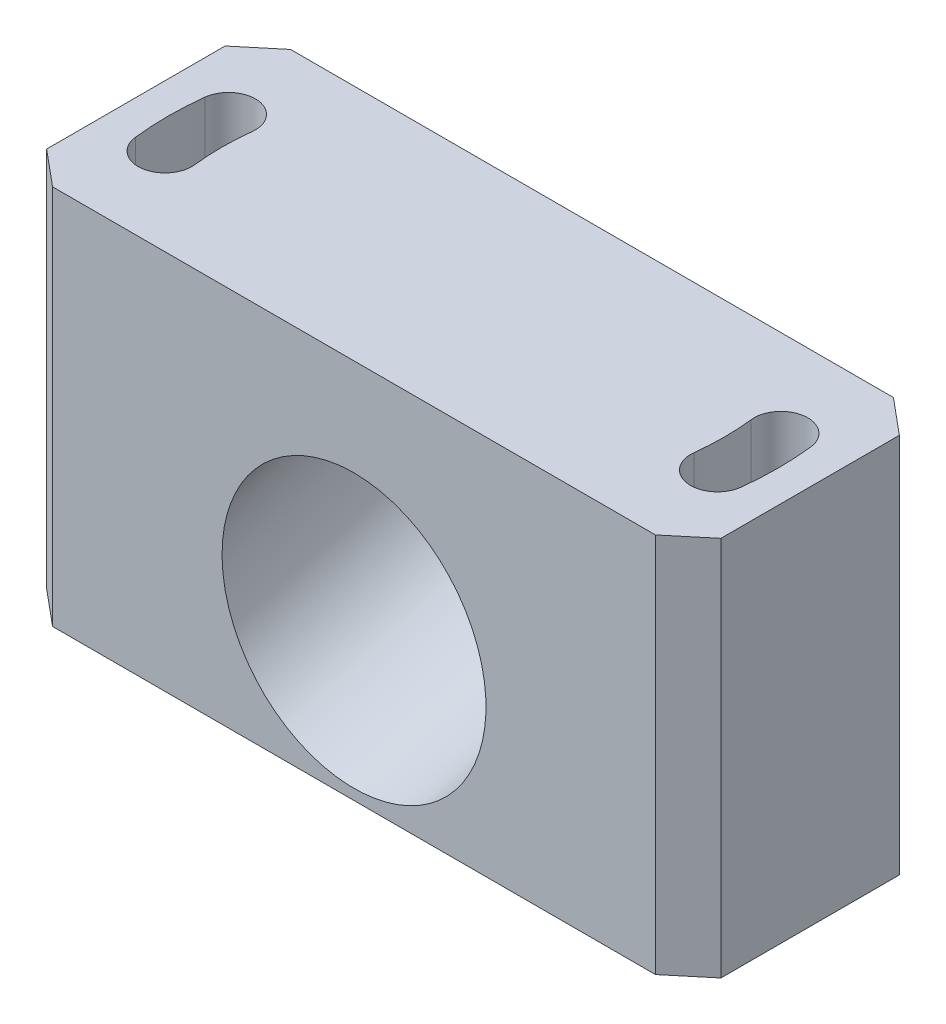
SolidWorks part; units mm, degrees
other "Markup1"
sketch "Sketch7" plane through (36.13, 27.5, 36.13) normal (0.3007, 0.0367, 0.953) x (0.9522, -0.0679, -0.2978)
ref_plane "Front Plane" through (0, 0, 0) normal (0, 0, 1) x (1, 0, 0)
ref_plane "Top Plane" through (0, 0, 0) normal (0, 1, 0) x (1, 0, 0)
ref_plane "Right Plane" through (0, 0, 0) normal (1, 0, 0) x (0, 0, -1)
sketch "Sketch2" plane through (0, 0, 0) normal (0, 0, 1) x (1, 0, 0)
  line L1 (-50, -27.5) -> (50, -27.5)
  line L2 (-50, -27.5) -> (-50, 27.5)
  line L3 (-50, 27.5) -> (50, 27.5)
  line L4 (50, -27.5) -> (50, 27.5)
  line L5 (-50, -27.5) -> (50, 27.5) construction
  line L6 (-50, 27.5) -> (50, -27.5) construction
  point P0 (0, 0)
  dimension "D1" = 100
  dimension "D2" = 55
extrude "Boss-Extrude1" add sketch "Sketch2" along normal mid plane 30
sketch "Sketch3" plane through (0, 0, 15) normal (0, 0, 1) x (1, 0, 0)
  line L2 (50, 27.5) -> (-50, 27.5) construction
  line L3 (-16, 27.5) -> (16, 27.5)
  arc A1 (-16, 27.5) -> (16, 27.5) centre (0, 27.5) ccw
  dimension "D2" = 16
sketch "Sketch5" plane through (0, 27.5, 0) normal (0, 1, 0) x (1, 0, 0)
  line L4 (-43.8772, 0) -> (42.7803, 0) construction
  circle A2 centre (0, 0) radius 35.05 construction
  arc A3 (-34.821, -4) -> (-34.821, 4) centre (0, 0) cw construction
  arc A4 (-38.1889, 4.3869) -> (-38.1889, -4.3869) centre (0, 0) ccw
  arc A5 (-31.4532, 3.6131) -> (-31.4532, -3.6131) centre (0, 0) ccw
  arc A6 (-31.4532, 3.6131) -> (-38.1889, 4.3869) centre (-34.821, 4) ccw
  arc A7 (-38.1889, -4.3869) -> (-31.4532, -3.6131) centre (-34.821, -4) ccw
  arc A8 (34.821, -4) -> (34.821, 4) centre (0, 0) ccw construction
  arc A9 (38.1889, -4.3869) -> (38.1889, 4.3869) centre (0, 0) ccw
  arc A10 (31.4532, -3.6131) -> (31.4532, 3.6131) centre (0, 0) ccw
  arc A11 (31.4532, -3.6131) -> (38.1889, -4.3869) centre (34.821, -4) ccw
  arc A12 (38.1889, 4.3869) -> (31.4532, 3.6131) centre (34.821, 4) ccw
  point P2 (-34.821, 4)
  point P3 (-34.821, -4)
  point P4 (34.821, 4)
  point P5 (34.821, -4)
  point P6 (-35.05, 0)
  point P20 (35.05, 0)
  dimension "D1" = 70.1
  dimension "D2" = 4
  dimension "D6" = 6.78
  dimension "D7" = 6.78
  dimension "D3" = 4
  dimension "D4" = 4
  dimension "D5" = 4
extrude "Cut-Extrude2" cut sketch "Sketch5" against normal through all
sketch "Sketch8" plane through (50, 0, 0) normal (1, 0, 0) x (0, 0, -1)
  line L0 (-15, -8) -> (15, -8) construction
  line L1 (-15, -27.5) -> (-15, 27.5) construction
  line L2 (15, -27.5) -> (15, 27.5) construction
  line L3 (-15, 27.5) -> (15, 27.5) construction
  circle A0 centre (0, -8) radius 16.7
  dimension "D2" = 33.4
  dimension "D1" = 35.5
ref_plane "Plane1" through (0, 5.5922, -20.8702) normal (0, 0.2588, -0.9659) x (-1, 0, 0)
sketch "Sketch9" plane through (0, 5.5922, -20.8702) normal (0, 0.2588, -0.9659) x (-1, 0, 0)
  line L0 (0, 0) -> (-15.3732, 0) construction
  line L1 (0, 0) -> (0, -11.1562) construction
  circle A0 centre (0, 2) radius 16.637
  dimension "D1" = 2
  dimension "D2" = 33.274
extrude "Cut-Extrude3" cut sketch "Sketch9" against normal through all
sketch "Sketch10" plane through (0, 27.5, 0) normal (0, 1, 0) x (1, 0, 0)
  line L0 (50, 15) -> (50, 5)
  line L1 (50, -15) -> (50, 15) construction
  line L2 (50, 5) -> (38, 15)
  line L3 (50, 15) -> (-50, 15) construction
  line L4 (38, 15) -> (50, 15)
  line L5 (50, -15) -> (38, -15)
  line L6 (50, -15) -> (-50, -15) construction
  line L7 (38, -15) -> (50, -5)
  line L8 (0, -15) -> (0, 15) construction
  line L9 (50, -5) -> (50, -15)
  line L10 (-50, 5) -> (-38, 15)
  line L11 (-50, 15) -> (-50, 5)
  line L12 (-38, 15) -> (-50, 15)
  line L13 (-38, -15) -> (-50, -5)
  line L14 (-50, -15) -> (-38, -15)
  line L15 (-50, -5) -> (-50, -15)
  line M10 (50, 15) -> (-50, 15)
  line M12 (-50, -15) -> (50, -15)
  line M13 (50, -15) -> (50, 15)
  dimension "D1" = 12
  dimension "D2" = 10
  dimension "D3" = 10
  dimension "D4" = 12
extrude "Cut-Extrude4" cut sketch "Sketch10" against normal through all contours L2 M13 M10 | L7 M12 M13 | L13 L15 L14 | L10 L12 L11
sketch "Sketch11" plane through (0, 27.5, 0) normal (0, 1, 0) x (1, 0, 0)
  line L0 (-42.5, 11.25) -> (-42.5, -11.25)
  line L1 (-50, 5) -> (-38, 15) construction
  line L2 (-38, -15) -> (-50, -5) construction
  line L3 (42.5, 11.25) -> (42.5, -11.25)
  line L4 (50, 5) -> (38, 15) construction
  line L5 (38, -15) -> (50, -5) construction
  line L6 (-42.5, 11.25) -> (-50, 5)
  line L7 (-50, 5) -> (-50, -5)
  line L8 (-50, -5) -> (-50, 5) construction
  line L10 (42.5, 11.25) -> (50, 5)
  line L11 (50, 5) -> (50, -5)
  line L12 (50, -5) -> (42.5, -11.25)
  line L13 (-50, -5) -> (-42.5, -11.25)
  dimension "D1" = 42.5
  dimension "D2" = 42.5
  dimension "D3" = 9.7628
extrude "Cut-Extrude5" cut sketch "Sketch11" against normal through all
sketch "Sketch12" plane through (0, -27.5, 0) normal (0, -1, 0) x (1, 0, 0)
  line L1 (-45.5, 17.5) -> (45.5, 17.5)
  line L2 (-45.5, 17.5) -> (-45.5, -17.5)
  line L3 (-45.5, -17.5) -> (45.5, -17.5)
  line L4 (45.5, 17.5) -> (45.5, -17.5)
  line L5 (-45.5, 17.5) -> (45.5, -17.5) construction
  line L6 (-45.5, -17.5) -> (45.5, 17.5) construction
  point P0 (0, 0)
  dimension "D1" = 17.5
  dimension "D2" = 45.5
extrude "Cut-Extrude6" cut sketch "Sketch12" against normal blind 7
